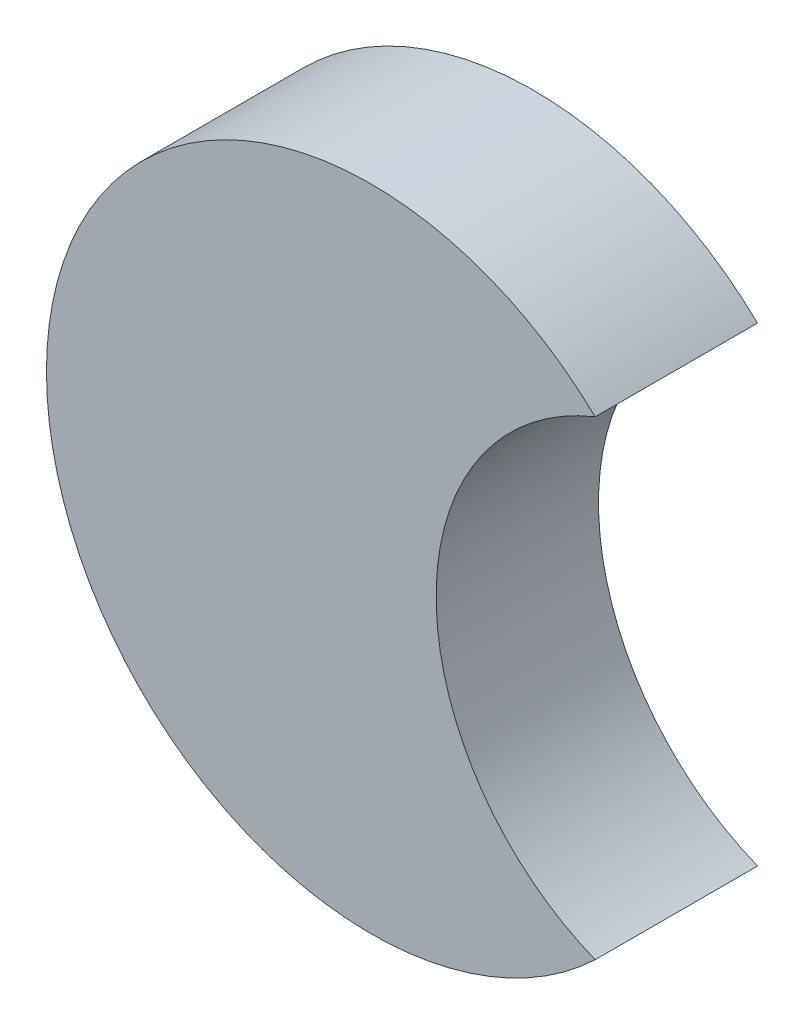
SolidWorks part; units mm, degrees
ref_plane "Front Plane" through (0, 0, 0) normal (0, 0, 1) x (1, 0, 0)
ref_plane "Top Plane" through (0, 0, 0) normal (0, 1, 0) x (1, 0, 0)
ref_plane "Right Plane" through (0, 0, 0) normal (1, 0, 0) x (0, 0, -1)
sketch "Sketch1" plane through (0, 0, 0) normal (0, 0, 1) x (1, 0, 0)
  circle A0 centre (0, 0) radius 50
extrude "Boss-Extrude1" add sketch "Sketch1" along normal blind 25
sketch "Sketch2" plane through (0, 0, 25) normal (0, 0, 1) x (1, 0, 0)
  circle A0 centre (49, 0) radius 39
extrude "Cut-Extrude1" cut sketch "Sketch2" against normal blind 25
